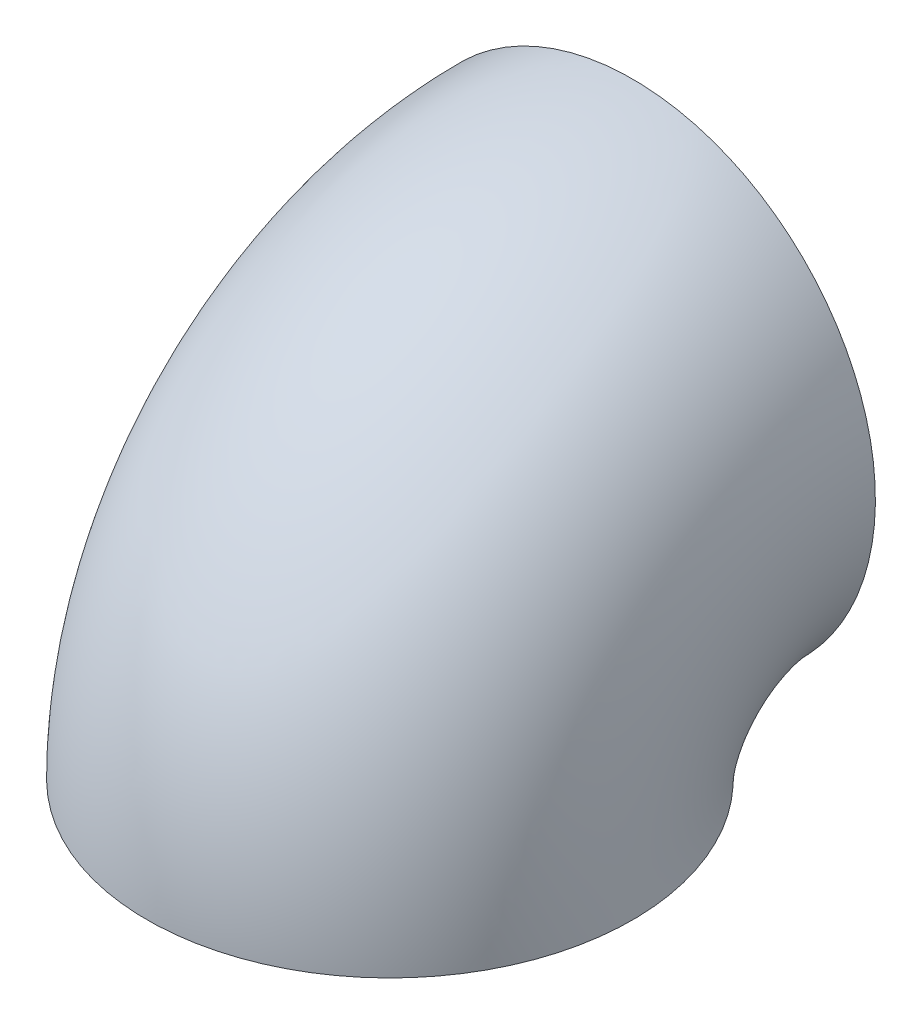
SolidWorks part; units mm, degrees
ref_plane "Front Plane" through (0, 0, 0) normal (0, 0, 1) x (1, 0, 0)
ref_plane "Top Plane" through (0, 0, 0) normal (0, 1, 0) x (1, 0, 0)
ref_plane "Right Plane" through (0, 0, 0) normal (1, 0, 0) x (0, 0, -1)
sketch "Sketch1" plane through (0, 0, 0) normal (1, 0, 0) x (0, 0, -1)
  arc A0 (0, 45) -> (-45, 0) centre (0, 0) ccw
  dimension "D1" = 45
sketch "Sketch2" plane through (0, 0, 0) normal (0, 1, 0) x (1, 0, 0)
  line L0 (0, -45) -> (0, 0) construction
  circle A0 centre (0, -45) radius 45
  circle A1 centre (0, -45) radius 10
  dimension "D1" = 90
  dimension "D2" = 20
sweep "Sweep1" add profiles "Sketch2" path "Sketch1"
